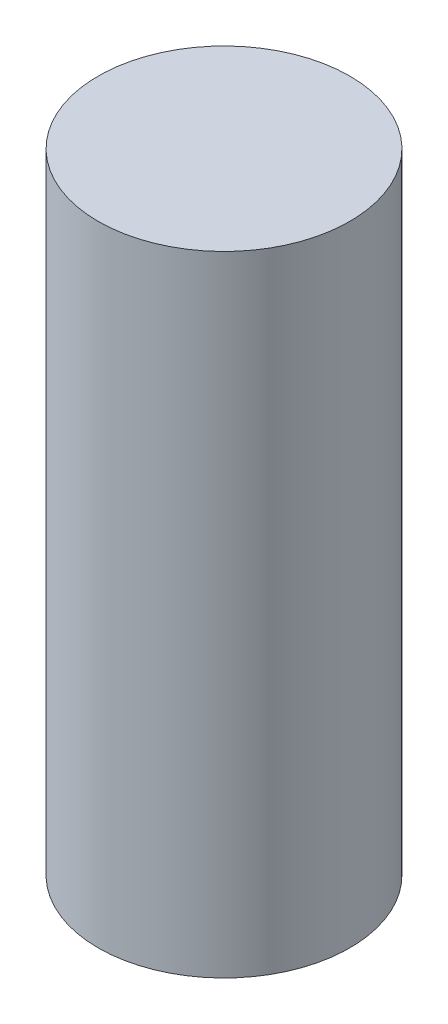
SolidWorks part; units mm, degrees
ref_plane "前视基准面" through (0, 0, 0) normal (0, 0, 1) x (1, 0, 0)
ref_plane "上视基准面" through (0, 0, 0) normal (0, 1, 0) x (1, 0, 0)
ref_plane "右视基准面" through (0, 0, 0) normal (1, 0, 0) x (0, 0, -1)
other "Configuration Table"
sketch "草图1" plane through (0, 0, 0) normal (0, 0, 1) x (1, 0, 0)
  line L0 (0, 0) -> (6, 0)
  line L1 (6, 0) -> (6, 30)
  line L2 (6, 30) -> (0, 30)
  line L3 (0, 30) -> (0, 0)
  line L4 (0, 0) -> (0, 30) construction
  dimension "radius" = 6
  dimension "height" = 30
revolve "Revolve" add sketch "草图1" angle 360 about L4
